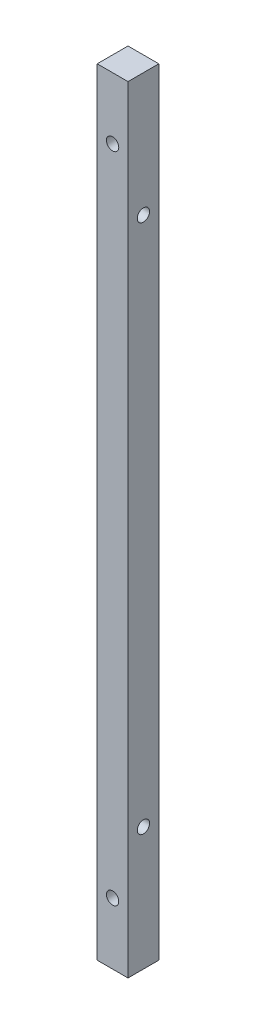
SolidWorks part; units mm, degrees
ref_plane "前视基准面" through (0, 0, 0) normal (0, 0, 1) x (1, 0, 0)
ref_plane "上视基准面" through (0, 0, 0) normal (0, 1, 0) x (1, 0, 0)
ref_plane "右视基准面" through (0, 0, 0) normal (1, 0, 0) x (0, 0, -1)
sketch "草图1" plane through (0, 0, 0) normal (0, 0, 1) x (1, 0, 0)
  line L1 (0, 0) -> (-5, 0)
  line L2 (0, 0) -> (0, 126)
  line L3 (0, 126) -> (-5, 126)
  line L4 (-5, 0) -> (-5, 126)
extrude "凸台-拉伸1" add sketch "草图1" along normal blind 5
sketch "草图2" plane through (0, 0, 5) normal (0, 0, 1) x (1, 0, 0)
  line L0 (0, 126) -> (-5, 126) construction
  line L1 (-5, 0) -> (0, 0) construction
  circle A1 centre (-2.5, 116) radius 1
  circle A2 centre (-2.5, 10) radius 1
  dimension "D1" = 10
  dimension "D2" = 10
extrude "切除-拉伸1" cut sketch "草图2" against normal blind 5
sketch "草图3" plane through (0, 0, 0) normal (1, 0, 0) x (0, 0, -1)
  line L0 (-5, 0) -> (0, 0) construction
  line L1 (-5, 126) -> (0, 126) construction
  circle A0 centre (-2.5, 106) radius 1
  circle A1 centre (-2.5, 20) radius 1
  dimension "D1" = 20
  dimension "D2" = 20
extrude "切除-拉伸2" cut sketch "草图3" against normal blind 5
